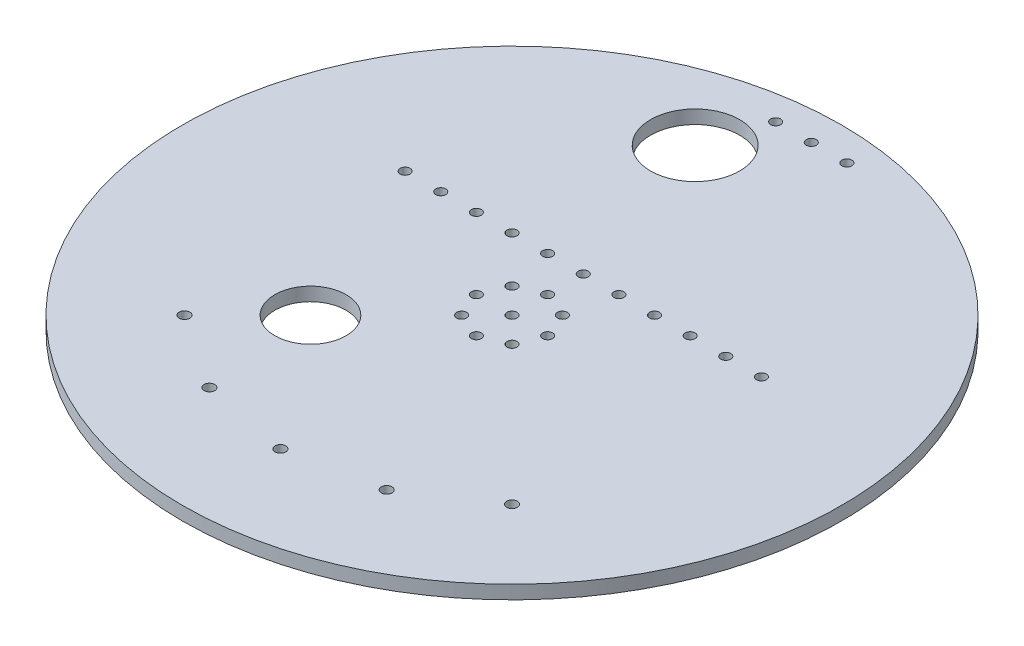
SolidWorks part; units mm, degrees
material "Balsa"
ref_plane "Front Plane" through (0, 0, 0) normal (0, 0, 1) x (1, 0, 0)
ref_plane "Top Plane" through (0, 0, 0) normal (0, 1, 0) x (1, 0, 0)
ref_plane "Right Plane" through (0, 0, 0) normal (1, 0, 0) x (0, 0, -1)
sketch "Sketch1" plane through (0, 0, 0) normal (0, 1, 0) x (1, 0, 0)
  circle A0 centre (0, 0) radius 117.475
  dimension "D1" = 234.95
extrude "Boss-Extrude1" add sketch "Sketch1" against normal blind 4.826
sketch "Sketch3" plane through (0, 0, 0) normal (0, 1, 0) x (1, 0, 0)
  line L1 (-114.4075, 26.67) -> (-88.9, 26.67)
  line L2 (0, -92.075) -> (0, -117.475)
  line L3 (-88.9, -26.67) -> (-88.9, 26.67)
  line L4 (0, 0) -> (-88.9, 0) construction
  line L5 (0, 0) -> (0, -117.475) construction
  line L6 (0, 0) -> (0, 117.475) construction
  line L8 (-88.9, -26.67) -> (-114.4075, -26.67)
  line L10 (-84.6624, -36.195) -> (-111.76, -36.195)
  arc A0 (-114.4075, 26.67) -> (-114.4075, -26.67) centre (0, 0) ccw
  circle A1 centre (0, 0) radius 117.475 construction
  arc A3 (-84.6624, -36.195) -> (0, -92.075) centre (0, 0) ccw
  arc A4 (-111.76, -36.195) -> (0, -117.475) centre (0, 0) ccw
  dimension "D1" = 88.9
  dimension "D2" = 53.34
  dimension "D4" = 9.525
  dimension "D5" = 25.4
extrude "Cut-Extrude4" [suppressed] cut sketch "Sketch3" against normal through all
sketch "Sketch4" [suppressed] plane through (0, 0, 0) normal (0, 1, 0) x (1, 0, 0)
  line L0 (-76.2, 38.1) -> (-76.2, 25.4) construction
  line L1 (-76.2, 25.4) -> (-76.2, 12.7) construction
  line L2 (-76.2, 12.7) -> (-76.2, 0) construction
  line L3 (-76.2, 0) -> (-76.2, -12.7) construction
  line L4 (-76.2, -12.7) -> (-76.2, -25.4) construction
  line L5 (-76.2, -25.4) -> (-76.2, -38.1) construction
  line L6 (0, 0) -> (-76.2, 0) construction
  line L7 (-76.2, -12.7) -> (-88.9, -12.7) construction
  line L11 (-88.9, -26.67) -> (-88.9, 26.67) construction
  line L12 (-76.2, 76.2) -> (-76.2, 63.5) construction
  line L13 (-76.2, 63.5) -> (-76.2, 50.8) construction
  line L14 (-76.2, 50.8) -> (-76.2, 38.1) construction
  circle A0 centre (-76.2, 0) radius 1.778
  circle A1 centre (-76.2, 12.7) radius 1.778
  circle A2 centre (-76.2, 25.4) radius 1.778
  circle A3 centre (-76.2, 38.1) radius 1.778
  circle A4 centre (-76.2, -12.7) radius 1.778
  circle A5 centre (-76.2, -25.4) radius 1.778
  circle A6 centre (-76.2, -38.1) radius 1.778
  circle A7 centre (-76.2, 50.8) radius 1.778
  circle A8 centre (-76.2, 63.5) radius 1.778
  circle A9 centre (-76.2, 76.2) radius 1.778
  dimension "D2" = 3.556
  dimension "D1" = 12.7
  dimension "D3" = 76.2
extrude "Cut-Extrude5" [suppressed] cut sketch "Sketch4" against normal through all
sketch "Sketch5" plane through (0, 0, 0) normal (0, 1, 0) x (1, 0, 0)
  circle A0 centre (0, 0) radius 1.778
  dimension "D1" = 3.556
extrude "Cut-Extrude6" cut sketch "Sketch5" against normal through all
sketch "Sketch6" plane through (0, 0, 0) normal (0, 1, 0) x (1, 0, 0)
  line L0 (0, 0) -> (0, 25.4) construction
  line L1 (0, 25.4) -> (12.7, 25.4) construction
  line L2 (12.7, 25.4) -> (25.4, 25.4) construction
  line L3 (25.4, 25.4) -> (38.1, 25.4) construction
  line L4 (-38.1, 25.4) -> (-50.8, 25.4) construction
  line L5 (38.1, 25.4) -> (50.8, 25.4) construction
  line L6 (0, 25.4) -> (-12.7, 25.4) construction
  line L7 (-12.7, 25.4) -> (-25.4, 25.4) construction
  line L8 (-25.4, 25.4) -> (-38.1, 25.4) construction
  line L9 (-50.8, 25.4) -> (-63.5, 25.4) construction
  line L10 (50.8, 25.4) -> (63.5, 25.4) construction
  line L11 (0, 106.68) -> (12.7, 106.68) construction
  line L12 (12.7, 106.68) -> (25.4, 106.68) construction
  line L13 (25.4, 106.68) -> (38.1, 106.68) construction
  line L14 (-38.1, 106.68) -> (-50.8, 106.68) construction
  line L15 (38.1, 106.68) -> (50.8, 106.68) construction
  line L16 (0, 106.68) -> (-12.7, 106.68) construction
  line L17 (-12.7, 106.68) -> (-25.4, 106.68) construction
  line L18 (-25.4, 106.68) -> (-38.1, 106.68) construction
  line L19 (-50.8, 106.68) -> (-63.5, 106.68) construction
  line L20 (50.8, 106.68) -> (63.5, 106.68) construction
  line L21 (0, 25.4) -> (0, 106.68) construction
  circle A0 centre (0, 25.4) radius 1.778
  circle A1 centre (-12.7, 25.4) radius 1.778
  circle A2 centre (-25.4, 25.4) radius 1.778
  circle A3 centre (-38.1, 25.4) radius 1.778
  circle A4 centre (12.7, 25.4) radius 1.778
  circle A5 centre (25.4, 25.4) radius 1.778
  circle A6 centre (38.1, 25.4) radius 1.778
  circle A7 centre (-50.8, 25.4) radius 1.778
  circle A8 centre (50.8, 25.4) radius 1.778
  circle A9 centre (-63.5, 25.4) radius 1.778
  circle A10 centre (63.5, 25.4) radius 1.778
  circle A11 centre (0, 106.68) radius 1.778
  circle A12 centre (-12.7, 106.68) radius 1.778
  circle A13 centre (-25.4, 106.68) radius 1.778 construction
  circle A14 centre (-38.1, 106.68) radius 1.778 construction
  circle A15 centre (12.7, 106.68) radius 1.778
  circle A16 centre (25.4, 106.68) radius 1.778 construction
  circle A17 centre (38.1, 106.68) radius 1.778 construction
  circle A18 centre (-50.8, 106.68) radius 1.778 construction
  circle A19 centre (50.8, 106.68) radius 1.778 construction
  circle A20 centre (-63.5, 106.68) radius 1.778 construction
  circle A21 centre (63.5, 106.68) radius 1.778 construction
  dimension "D1" = 3.556
  dimension "D4" = 3.556
  dimension "D2" = 12.7
  dimension "D3" = 25.4
  dimension "D5" = 12.7
  dimension "D6" = 81.28
extrude "Cut-Extrude7" cut sketch "Sketch6" against normal through all
sketch "Sketch7" plane through (0, 0, 0) normal (0, 1, 0) x (1, 0, 0)
  line L0 (-8.9803, 8.9803) -> (0, 0) construction
  line L1 (0, 0) -> (8.9803, -8.9803) construction
  line L3 (8.9803, 8.9803) -> (0, 0) construction
  line L4 (0, 0) -> (-8.9803, -8.9803) construction
  line L6 (-12.7, 0) -> (0, 0) construction
  line L7 (0, 0) -> (0, 12.7) construction
  line L9 (12.7, 0) -> (0, 0) construction
  line L10 (0, 0) -> (0, -12.7) construction
  circle A0 centre (0, 12.7) radius 1.778
  circle A1 centre (12.7, 0) radius 1.778
  circle A2 centre (0, -12.7) radius 1.778
  circle A3 centre (-12.7, 0) radius 1.778
  circle A4 centre (-8.9803, 8.9803) radius 1.778
  circle A5 centre (8.9803, 8.9803) radius 1.778
  circle A6 centre (8.9803, -8.9803) radius 1.778
  circle A7 centre (-8.9803, -8.9803) radius 1.778
  dimension "D1" = 45
  dimension "D2" = 3.556
  dimension "D3" = 12.7
extrude "Cut-Extrude8" cut sketch "Sketch7" against normal through all
sketch "Sketch8" plane through (0, 0, 0) normal (0, 1, 0) x (1, 0, 0)
  line L0 (0, 0) -> (-35.921, -35.921) construction
  line L1 (-35.921, -35.921) -> (-35.921, -1.2798) construction
  circle A0 centre (-35.921, -35.921) radius 12.7
  dimension "D3" = 25.4
  dimension "D1" = 45
  dimension "D2" = 50.8
extrude "Cut-Extrude9" cut sketch "Sketch8" against normal through all
mirror "Mirror1" [suppressed] about plane through (0, 0, 0) normal (1, 0, 0)
mirror "Mirror3" [suppressed] about plane through (0, 0, 0) normal (1, 0, 0)
sketch "Sketch9" plane through (0, 0, 0) normal (0, 1, 0) x (1, 0, 0)
  line L4 (0, -82.55) -> (0, 0) construction
  circle A1 centre (0, -82.55) radius 1.905
  dimension "D2" = 3.81
  dimension "D1" = 82.55
extrude "Cut-Extrude10" cut sketch "Sketch9" against normal through all
pattern_circular "CirPattern1" count 3 over 45 about axis through (0, 0, 0) along (0, 1, 0) of "Cut-Extrude10"
pattern_circular "CirPattern2" count 3 over 45 about axis through (0, 0, 0) along (0, 1, 0) of "Cut-Extrude10"
sketch "Sketch10" plane through (0, 0, 0) normal (0, 1, 0) x (1, 0, 0)
  line L0 (-19.812, 85.09) -> (-19.812, 0) construction
  line L1 (-19.812, 0) -> (0, 0) construction
  circle A0 centre (-19.812, 85.09) radius 15.875
  dimension "D1" = 31.75
  dimension "D2" = 85.09
  dimension "D3" = 19.812
extrude "Cut-Extrude11" cut sketch "Sketch10" against normal through all
